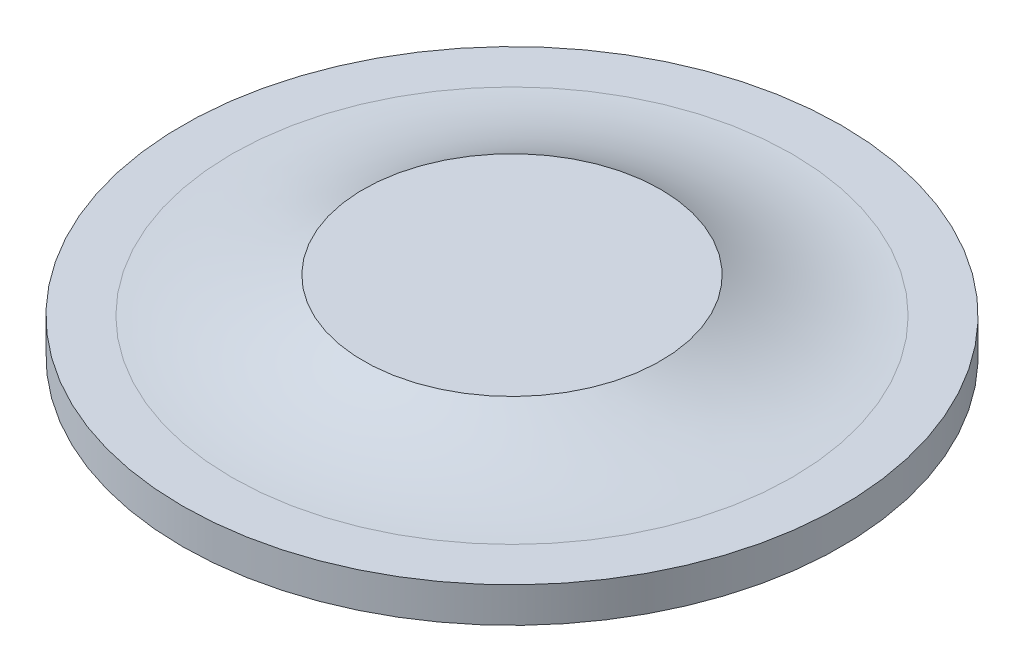
SolidWorks part; units mm, degrees
ref_plane "Front Plane" through (0, 0, 0) normal (0, 0, 1) x (1, 0, 0)
ref_plane "Top Plane" through (0, 0, 0) normal (0, 1, 0) x (1, 0, 0)
ref_plane "Right Plane" through (0, 0, 0) normal (1, 0, 0) x (0, 0, -1)
sketch "Sketch1" plane through (0, 0, 0) normal (1, 0, 0) x (0, 0, -1)
  line L0 (0, 0) -> (75, 0)
  line L1 (75, 0) -> (75, 8)
  line L2 (0, 0) -> (0, 16)
  line L3 (-75, 8) -> (-63.75, 8)
  line L4 (63.75, 8) -> (75, 8)
  line L5 (63.75, 8) -> (75, 8)
  line L6 (-75, 8) -> (-63.75, 8)
  line L7 (33.8293, 16) -> (0, 16)
  arc A0 (-63.75, 8) -> (-33.8293, 16) centre (-63.75, 67.9531) ccw
  arc A1 (33.8293, 16) -> (63.75, 8) centre (63.75, 67.9531) ccw
  arc A2 (33.8293, 16) -> (63.75, 8) centre (63.75, 67.9531) ccw
  arc A3 (-63.75, 8) -> (-33.8293, 16) centre (-63.75, 67.9531) ccw
revolve "Revolve1" add sketch "Sketch1" angle 360 about L2
